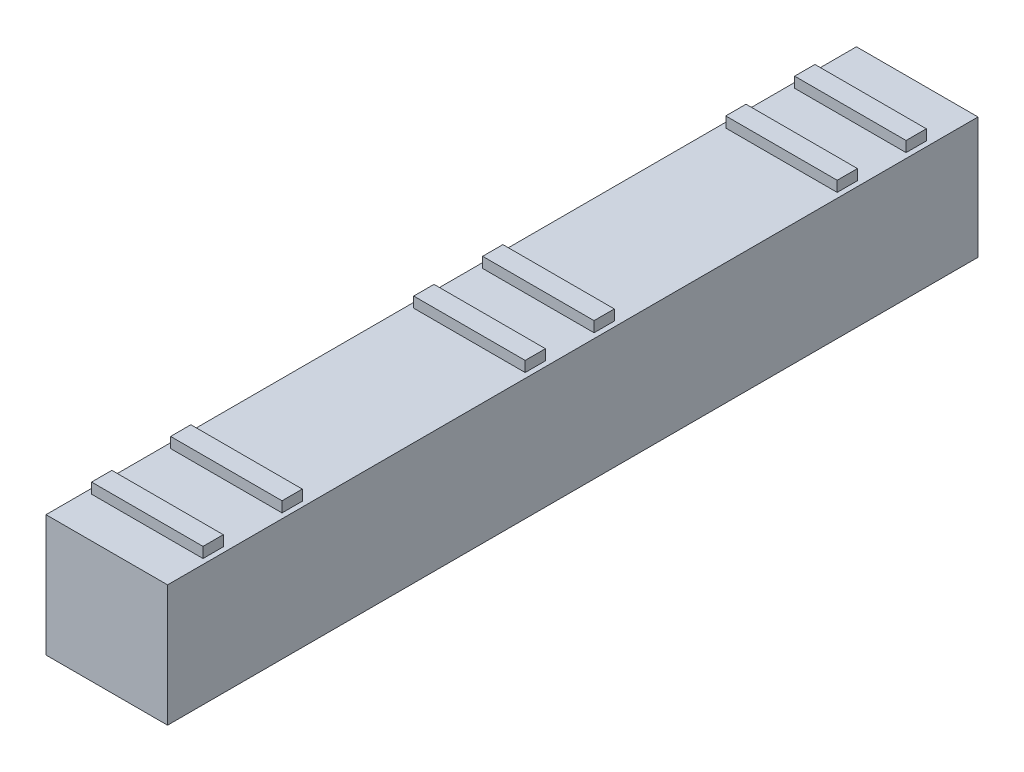
SolidWorks part; units mm, degrees
ref_plane "Front Plane" through (0, 0, 0) normal (0, 0, 1) x (1, 0, 0)
ref_plane "Top Plane" through (0, 0, 0) normal (0, 1, 0) x (1, 0, 0)
ref_plane "Right Plane" through (0, 0, 0) normal (1, 0, 0) x (0, 0, -1)
sketch "Sketch1" plane through (0, 0, 0) normal (0, 1, 0) x (1, 0, 0)
  line L1 (-15, -100) -> (15, -100)
  line L2 (-15, -100) -> (-15, 100)
  line L3 (-15, 100) -> (15, 100)
  line L4 (15, -100) -> (15, 100)
  line L5 (-15, -100) -> (15, 100) construction
  line L6 (-15, 100) -> (15, -100) construction
  point P0 (0, 0)
  dimension "D1" = 200
  dimension "D2" = 30
extrude "Boss-Extrude1" add sketch "Sketch1" along normal blind 30
sketch "Sketch3" plane through (0, 30, 0) normal (0, 1, 0) x (1, 0, 0)
  line L0 (-15, -100) -> (15, -100) construction
  line L1 (-13.75, -85) -> (13.75, -85)
  line L2 (-13.75, -85) -> (-13.75, -90)
  line L3 (-13.75, -90) -> (13.75, -90)
  line L4 (13.75, -85) -> (13.75, -90)
  line L5 (-13.75, -85) -> (13.75, -90) construction
  line L6 (-13.75, -90) -> (13.75, -85) construction
  point P0 (0, -87.5)
  point P5 (0, -86.79)
  dimension "D1" = 27.5
  dimension "D2" = 5
  dimension "D3" = 10
extrude "Boss-Extrude2" add sketch "Sketch3" along normal blind 2.6
sketch "Sketch4" plane through (0, 30, 0) normal (0, 1, 0) x (1, 0, 0)
  line L0 (0, 100) -> (0, -100)
  line L1 (15, 100) -> (-15, 100) construction
  line L2 (-15, -100) -> (15, -100) construction
  line L3 (13.75, -85) -> (-13.75, -85) construction
  point P6 (0, -68)
  point P7 (0, -8)
  point P8 (0, 9)
  point P9 (0, 69)
  point P10 (0, 86)
  dimension "D1" = 17
  dimension "D2" = 60
  dimension "D3" = 17
  dimension "D4" = 60
  dimension "D5" = 17
pattern_sketch "Sketch-Pattern1" of "Boss-Extrude2" driven by "Sketch4"
